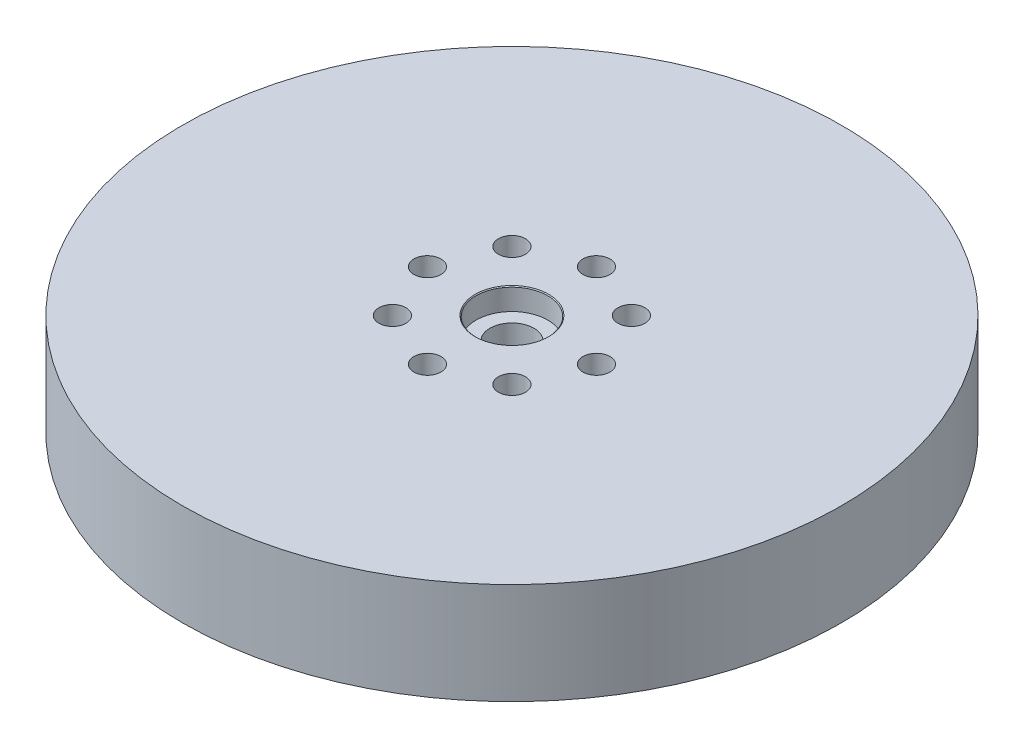
SolidWorks part; units mm, degrees
material "Ст 3 ГОСТ 380-88"
ref_plane "Front Plane" through (0, 0, 0) normal (0, 0, 1) x (1, 0, 0)
ref_plane "Top Plane" through (0, 0, 0) normal (0, 1, 0) x (1, 0, 0)
ref_plane "Right Plane" through (0, 0, 0) normal (1, 0, 0) x (0, 0, -1)
sketch "Sketch1" plane through (0, 0, 0) normal (1, 0, 0) x (0, 0, -1)
  line L0 (0, -14) -> (0, -31.7786) construction
  line L1 (-195, 60) -> (-195, 0)
  line L2 (-195, 0) -> (-185.5, 0)
  line L3 (-74.5, 0) -> (-74.5, -14)
  line L4 (-74.5, -14) -> (-15.5, -14)
  line L5 (-195, 60) -> (-185.5, 60)
  line L6 (0, 30.6711) -> (0, 60) construction
  line L7 (-13, 47) -> (-13, -11.5)
  line L8 (-13, -14) -> (0, -14) construction
  line L9 (0, 30.6711) -> (0, -14) construction
  line L10 (0, -14) -> (0, 30.6711) construction
  line L11 (-13, 60) -> (0, 60) construction
  line L12 (-15.5, 60) -> (-13, 57.5) construction
  line L13 (-15.5, -14) -> (-13, -11.5)
  line L14 (-21.25, 59.5) -> (-21.25, 47)
  line L15 (-21.25, 47) -> (-13, 47)
  line L16 (-21.25, 60) -> (-15.5, 60) construction
  line L17 (-13, 57.5) -> (-13, 47) construction
  line L18 (-21.75, 60) -> (-21.25, 59.5)
  line L19 (-185.5, 0) -> (-185.5, 10)
  line L20 (-185.5, 10) -> (-74.5, 10)
  line L21 (-74.5, 0) -> (-74.5, 10)
  line L22 (-185.5, 0) -> (-74.5, 0) construction
  line L23 (-185.5, 60) -> (-185.5, 50) construction
  line L24 (-185.5, 50) -> (-74.5, 50) construction
  line L25 (-74.5, 50) -> (-74.5, 60) construction
  line L26 (-185.5, 60) -> (-74.5, 60) construction
  line L27 (-74.5, 60) -> (-21.75, 60)
  line L28 (-185.5, 60) -> (-74.5, 60)
  dimension "D1" = 60
  dimension "D2" = 390
  dimension "D3" = 149
  dimension "D4" = 14
  dimension "D5" = 13
  dimension "D6" = 13
  dimension "D7" = 42.5
  dimension "D10" = 10
  dimension "D11" = 9.5
  dimension "D13" = 10
revolve "Revolve1" add sketch "Sketch1" angle 360 about L0
sketch "Sketch2" plane through (0, 60, 0) normal (0, 1, 0) x (1, 0, 0)
  line L0 (-50, 0) -> (0, 0) construction
  circle A0 centre (-50, 0) radius 4
  circle A1 centre (-35.3553, 35.3553) radius 4
  circle A2 centre (0, 50) radius 4
  circle A3 centre (35.3553, 35.3553) radius 4
  circle A4 centre (50, 0) radius 4
  circle A5 centre (35.3553, -35.3553) radius 4
  circle A6 centre (0, -50) radius 4
  circle A7 centre (-35.3553, -35.3553) radius 4
  point P21 (0, 0)
  dimension "D1" = 8
  dimension "D2" = 8
  dimension "D3" = 50
extrude "Cut-Extrude1" cut sketch "Sketch2" against normal through all both and the other way through all
sketch "Sketch3" plane through (0, 10, 0) normal (0, -1, 0) x (1, 0, 0)
  line L0 (0, 129.2853) -> (0, -136.9499) construction
  line L1 (0, 0) -> (0, 132.1781) construction
  line L2 (0, 0) -> (-104.479, 104.479) construction
  circle A0 centre (0, 82) radius 2
  circle A1 centre (0, 120) radius 2
  circle A2 centre (84.8528, 84.8528) radius 2
  circle A3 centre (57.9828, 57.9828) radius 2 construction
  circle A4 centre (120, 0) radius 2
  circle A5 centre (82, 0) radius 2
  circle A6 centre (84.8528, -84.8528) radius 2
  circle A7 centre (57.9828, -57.9828) radius 2 construction
  circle A8 centre (0, -120) radius 2
  circle A9 centre (0, -82) radius 2
  circle A10 centre (-84.8528, -84.8528) radius 2
  circle A11 centre (-57.9828, -57.9828) radius 2 construction
  circle A12 centre (-120, 0) radius 2
  circle A13 centre (-82, 0) radius 2
  circle A14 centre (-84.8528, 84.8528) radius 2
  circle A15 centre (-57.9828, 57.9828) radius 2 construction
  circle A16 centre (0, 0) radius 120 construction
  point P104 (0, 0)
  dimension "D1" = 4
  dimension "D4" = 120
  dimension "D3" = 240
  dimension "D2" = 82
  dimension "D6" = 45
  dimension "D5" = 8
extrude "Cut-Extrude2" [suppressed] cut sketch "Sketch3" against normal blind 15
ref_plane "Plane1" through (0, 30, 0) normal (0, -1, 0) x (-1, 0, 0)
mirror "Mirror1" [suppressed] about plane through (0, 30, 0) normal (0, -1, 0)
sketch "Sketch4" plane through (0, 60, 0) normal (0, 1, 0) x (1, 0, 0)
  circle A0 centre (0, 50) radius 8
  circle A1 centre (0, 0) radius 50 construction
  circle A2 centre (35.3553, 35.3553) radius 8
  circle A3 centre (50, 0) radius 8
  circle A4 centre (35.3553, -35.3553) radius 8
  circle A5 centre (0, -50) radius 8
  circle A6 centre (-35.3553, -35.3553) radius 8
  circle A7 centre (-50, 0) radius 8
  circle A8 centre (-35.3553, 35.3553) radius 8
  point P22 (0, 0)
  dimension "D1" = 16
  dimension "D2" = 8
extrude "Cut-Extrude3" cut sketch "Sketch4" against normal blind 12
sketch "Sketch5" plane through (0, -14, 0) normal (0, -1, 0) x (1, 0, 0)
  circle A0 centre (35.3553, -35.3553) radius 4 construction
  circle A1 centre (0, 0) radius 74.5
  circle A2 centre (0, 0) radius 74.5
  circle A3 centre (0, -50) radius 4 construction
  circle A4 centre (-35.3553, -35.3553) radius 4 construction
  circle A5 centre (-50, 0) radius 4 construction
  circle A6 centre (50, 0) radius 4 construction
  circle A7 centre (35.3553, 35.3553) radius 4 construction
  circle A8 centre (-35.3553, 35.3553) radius 4 construction
  circle A9 centre (0, 50) radius 4 construction
  circle A10 centre (35.3553, -35.3553) radius 4
  circle A11 centre (0, -50) radius 4
  circle A12 centre (-35.3553, -35.3553) radius 4
  circle A13 centre (-50, 0) radius 4
  circle A14 centre (50, 0) radius 4
  circle A15 centre (35.3553, 35.3553) radius 4
  circle A16 centre (-35.3553, 35.3553) radius 4
  circle A17 centre (0, 50) radius 4
  circle A18 centre (0, 0) radius 13 construction
  circle A19 centre (0, 0) radius 13
  dimension "D1" = 0
extrude "Boss-Extrude1" add sketch "Sketch5" along normal blind 1 from offset 30 separate body
sketch "Sketch6" plane through (0, -14, 0) normal (0, -1, 0) x (1, 0, 0)
  circle A1 centre (0, 0) radius 74.5
  circle A2 centre (0, 0) radius 74.5
  dimension "D1" = 0
extrude "Cut-Extrude4" cut sketch "Sketch6" against normal blind 2.5
sketch "Sketch7" plane through (0, 10, 0) normal (0, -1, 0) x (1, 0, 0)
  line L0 (0, 234.4435) -> (0, -294.1465) construction
  line L1 (0, 0) -> (28.7013, 69.291) construction
  line L3 (-28.7013, 69.291) -> (-70.4138, 169.9938) construction
  line L4 (28.2387, 69.4808) -> (69.9516, 170.1845)
  line L5 (-28.2387, 69.4808) -> (-69.9516, 170.1845)
  line L6 (28.7013, 69.291) -> (70.4138, 169.9938) construction
  line L7 (70.9878, 171.3797) -> (89.9519, 217.1632) construction
  line L8 (70.4138, 169.9938) -> (70.9878, 171.3797) construction
  line L9 (0, 75) -> (22.6048, 75) construction
  line L10 (0, 129.5) -> (22.6048, 129.5) construction
  line L11 (0, 184) -> (132.4756, 184) construction
  circle A1 centre (0, 0) radius 13 construction
  arc A2 (69.9516, 170.1845) -> (-69.9516, 170.1845) centre (0, 0) ccw
  circle A3 centre (0, 157) radius 2.6
  circle A4 centre (0, 0) radius 185.5 construction
  circle A6 centre (0, 102) radius 2.6
  arc A8 (-69.9516, 170.1845) -> (-70.4138, 169.9938) centre (0, 0) ccw construction
  arc A9 (28.2387, 69.4808) -> (-28.2387, 69.4808) centre (0, 0) ccw
  dimension "D1" = 22.5
  dimension "D2" = 184
  dimension "D3" = 371
  dimension "D5" = 0.5
  dimension "D6" = 75
  dimension "D7" = 5.2
  dimension "D4" = 109
  dimension "D8" = 54.5
  dimension "D9" = 55
extrude "Boss-Extrude3" add sketch "Sketch7" along normal blind 5 from offset 0.01 separate body
sketch "Sketch8" plane through (0, 4.99, 0) normal (0, -1, 0) x (1, 0, 0)
  line L2 (28.2387, 69.4808) -> (69.9516, 170.1845)
  line L3 (-69.9516, 170.1845) -> (-28.2387, 69.4808)
  line L4 (28.2387, 69.4808) -> (69.9516, 170.1845)
  line L5 (-69.9516, 170.1845) -> (-28.2387, 69.4808)
  circle A0 centre (0, 102) radius 2.6 construction
  circle A1 centre (0, 157) radius 2.6 construction
  arc A2 (28.2387, 69.4808) -> (-28.2387, 69.4808) centre (0, 0) ccw
  arc A3 (69.9516, 170.1845) -> (-69.9516, 170.1845) centre (0, 0) ccw
  arc A4 (28.2387, 69.4808) -> (-28.2387, 69.4808) centre (0, 0) ccw
  arc A5 (69.9516, 170.1845) -> (-69.9516, 170.1845) centre (0, 0) ccw
  circle A6 centre (0, 102) radius 2.6
  circle A7 centre (0, 157) radius 2.6
  dimension "D1" = 0
extrude "Boss-Extrude4" add sketch "Sketch8" along normal blind 5 separate body
chamfer "Chamfer3" distance 3.5 angle 45 2 edges at (0, -0.01, 99.4) (0, -0.01, 154.4)
chamfer "Chamfer4" distance 3.5 angle 45 2 edges at (0, 9.99, 104.6) (0, 9.99, 154.4)
sketch "Sketch9" plane through (0, 10, 0) normal (0, -1, 0) x (1, 0, 0)
  line L0 (0, 0) -> (0, 213.1478) construction
  circle A0 centre (0, 157) radius 2.6
  circle A1 centre (0, 157) radius 2.6 construction
  circle A3 centre (0, 102) radius 2.6
  circle A4 centre (0, 102) radius 2.6 construction
  circle A5 centre (111.0158, 111.0158) radius 2.6
  circle A6 centre (72.1249, 72.1249) radius 2.6
  circle A7 centre (157, 0) radius 2.6
  circle A8 centre (102, 0) radius 2.6
  circle A9 centre (111.0158, -111.0158) radius 2.6
  circle A10 centre (72.1249, -72.1249) radius 2.6
  circle A11 centre (0, -157) radius 2.6
  circle A12 centre (0, -102) radius 2.6
  circle A13 centre (-111.0158, -111.0158) radius 2.6
  circle A14 centre (-72.1249, -72.1249) radius 2.6
  circle A15 centre (-157, 0) radius 2.6
  circle A16 centre (-102, 0) radius 2.6
  circle A17 centre (-111.0158, 111.0158) radius 2.6
  circle A18 centre (-72.1249, 72.1249) radius 2.6
  point P42 (0, 0)
  dimension "D1" = 5.2
  dimension "D2" = 8
extrude "Cut-Extrude5" cut sketch "Sketch9" against normal blind 15
sketch "Sketch10" plane through (0, -11.5, 0) normal (0, -1, 0) x (1, 0, 0)
  circle A0 centre (0, 0) radius 65
  circle A1 centre (0, 0) radius 35
  circle A2 centre (0, 50) radius 4 construction
  circle A3 centre (50, 0) radius 4 construction
  circle A4 centre (35.3553, -35.3553) radius 4 construction
  circle A5 centre (0, -50) radius 4 construction
  circle A6 centre (-35.3553, -35.3553) radius 4 construction
  circle A7 centre (-50, 0) radius 4 construction
  circle A8 centre (-35.3553, 35.3553) radius 4 construction
  circle A9 centre (35.3553, 35.3553) radius 4 construction
  circle A10 centre (50, 0) radius 4
  circle A11 centre (35.3553, -35.3553) radius 4
  circle A12 centre (0, -50) radius 4
  circle A13 centre (-35.3553, -35.3553) radius 4
  circle A14 centre (-50, 0) radius 4
  circle A15 centre (-35.3553, 35.3553) radius 4
  circle A16 centre (0, 50) radius 4
  circle A17 centre (35.3553, 35.3553) radius 4
  dimension "D1" = 130
  dimension "D2" = 70
extrude "Boss-Extrude5" add sketch "Sketch10" along normal blind 10
fillet "Fillet1" radius 1 13 edges at (0, -11.5, -74.5) (0, -11.5, -65) (35.3553, -21.5, 31.3553) (-35.3553, -21.5, 31.3553) (-35.3553, -21.5, -39.3553) (35.3553, -21.5, -39.3553) (0, -21.5, -35) (0, -21.5, -65) (50, -21.5, -4) (0, -21.5, -54) (-50, -21.5, -4) (0, -21.5, 46) (0, 10, 74.5)
